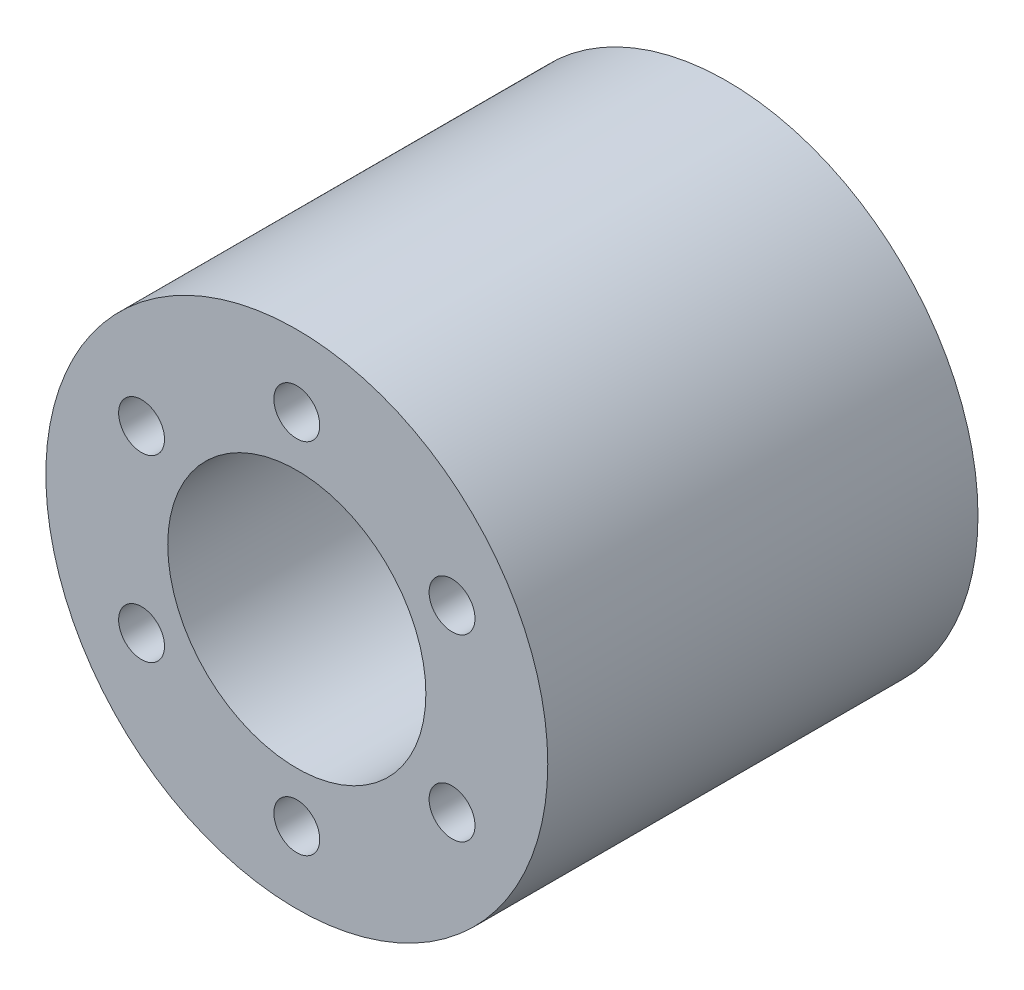
SolidWorks part; units mm, degrees
material "Custom Plastic"
ref_plane "Front Plane" through (0, 0, 0) normal (0, 0, 1) x (1, 0, 0)
ref_plane "Top Plane" through (0, 0, 0) normal (0, 1, 0) x (1, 0, 0)
ref_plane "Right Plane" through (0, 0, 0) normal (1, 0, 0) x (0, 0, -1)
sketch "Sketch1" plane through (0, 0, 0) normal (0, 0, 1) x (1, 0, 0)
  line L0 (0, 0) -> (0, 12.5) construction
  circle A0 centre (0, 0) radius 17.5
  circle A1 centre (0, 12.5) radius 1.6
  circle A2 centre (10.8253, 6.25) radius 1.6
  circle A3 centre (10.8253, -6.25) radius 1.6
  circle A4 centre (0, -12.5) radius 1.6
  circle A5 centre (-10.8253, -6.25) radius 1.6
  circle A6 centre (-10.8253, 6.25) radius 1.6
  circle A7 centre (0, 0) radius 9
  point P17 (0, 0)
  dimension "D1" = 35
  dimension "D3" = 3.2
  dimension "D5" = 18
  dimension "D2" = 12.5
  dimension "D4" = 6
extrude "Boss-Extrude1" add sketch "Sketch1" along normal blind 30
